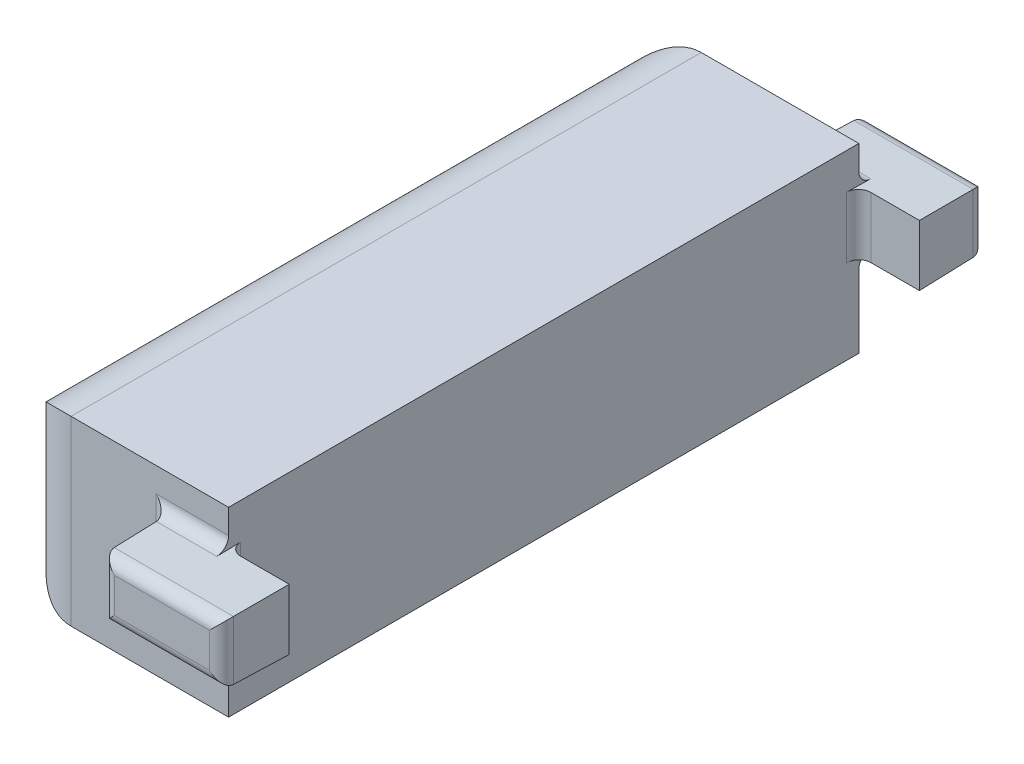
SolidWorks part; units mm, degrees
ref_plane "Front Plane" through (0, 0, 0) normal (0, 0, 1) x (1, 0, 0)
ref_plane "Top Plane" through (0, 0, 0) normal (0, 1, 0) x (1, 0, 0)
ref_plane "Right Plane" through (0, 0, 0) normal (1, 0, 0) x (0, 0, -1)
sketch "Sketch2" plane through (-12.65, 0, 0) normal (1, 0, 0) x (0, 0, -1)
  line L0 (55.8, 2.7) -> (55.8, 3.2) construction
  line L1 (55.9, 3.5) -> (61.1, 3.5)
  line L2 (55.9, 3.5) -> (55.9, 2)
  line L3 (55.9, 2) -> (61.1, 2)
  line L4 (61.1, 3.5) -> (61.1, 2)
  line L5 (61.2, 3.2) -> (61.2, 2.7) construction
  line L7 (68.4284, 3.6) -> (61.2, 3.6) construction
  line L8 (61.2, 2) -> (55.8, 2) construction
  dimension "D1" = 0.1
  dimension "D2" = 0.1
  dimension "D4" = 0.1
extrude "Boss-Extrude1" add sketch "Sketch2" against normal blind 1.3 and the other way blind 0.5
sketch "Sketch3" plane through (0, 0, -55.9) normal (0, 0, 1) x (1, 0, 0)
  line L1 (-11.65, 3.2) -> (-12.65, 3.2)
  line L2 (-11.65, 3.2) -> (-11.65, 2.6982)
  line L3 (-11.65, 2.6982) -> (-12.65, 2.6982)
  line L4 (-12.65, 3.2) -> (-12.65, 2.6982)
  point P4 (-12.718, 2.6982)
  point P5 (-12.6423, 3.1449)
  point P6 (0, 0)
  point P7 (0, 0)
  dimension "D4" = 1
extrude "Boss-Extrude2" add sketch "Sketch3" along normal blind 0.55 draft 1
ref_plane "Plane1" through (0, 0, -58.5) normal (0, 0, 1) x (1, 0, 0)
mirror "Mirror1" about plane through (0, 0, -58.5) normal (0, 0, 1) of "Boss-Extrude2"
fillet "Fillet1" radius 0.1 14 edges at (-12.15, 3.1904, -61.65) (-11.6596, 2.9491, -61.65) (-12.15, 2.7078, -61.65) (-11.6596, 2.9491, -55.35) (-12.15, 2.7078, -55.35) (-12.15, 3.1904, -55.35) (-12.6404, 2.9491, -55.35) (-12.6404, 2.9491, -61.65) (-12.4, 3.2, -61.1) (-12.4, 2.6982, -61.1) (-12.65, 2.9491, -61.1) (-12.4, 2.6982, -55.9) (-12.65, 2.9491, -55.9) (-12.4, 3.2, -55.9)
fillet "Fillet2" radius 0.1 2 edges at (-12.15, 2.9491, -55.9) (-12.15, 2.9491, -61.1)
fillet "Fillet3" radius 0.5 4 edges at (-13.95, 2, -58.5) (-13.95, 2.75, -61.1) (-13.95, 3.5, -58.5) (-13.95, 2.75, -55.9)
